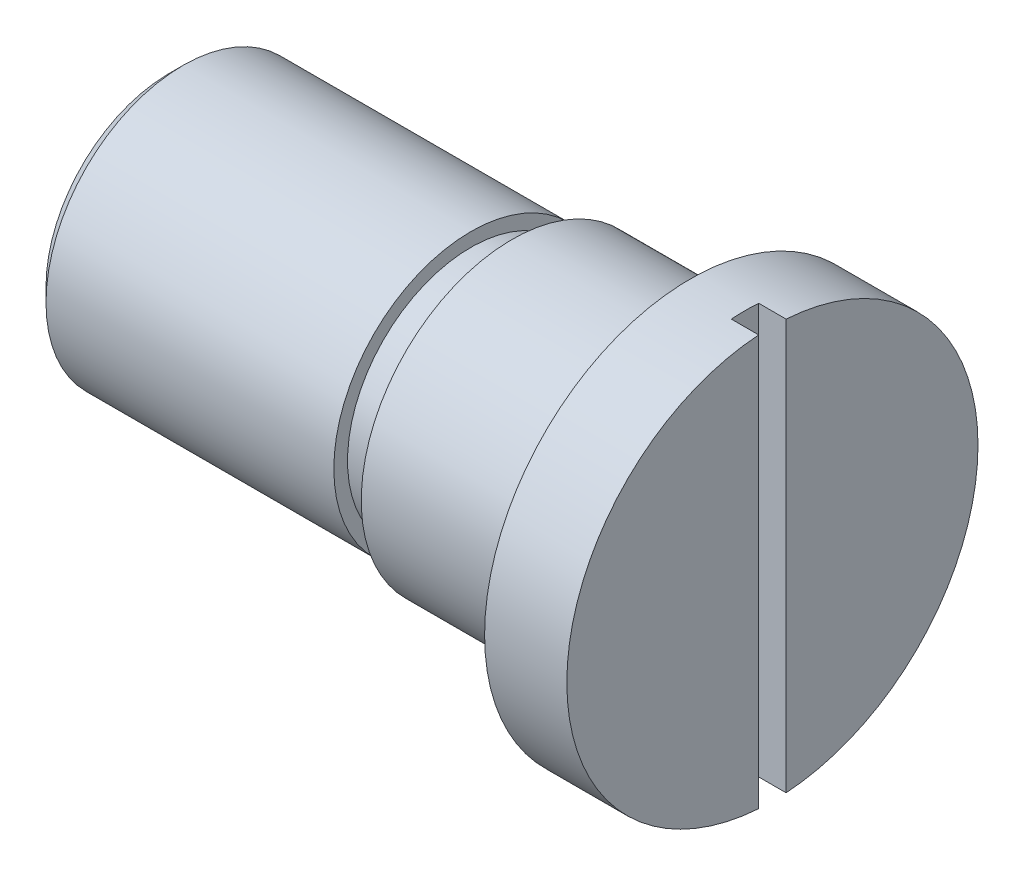
SolidWorks part; units mm, degrees
ref_plane "Ön Düzlem" through (0, 0, 0) normal (0, 0, 1) x (1, 0, 0)
ref_plane "Üst Düzlem" through (0, 0, 0) normal (0, 1, 0) x (1, 0, 0)
ref_plane "Sağ Düzlem" through (0, 0, 0) normal (1, 0, 0) x (0, 0, -1)
sketch "Çizim1" plane through (0, 0, 0) normal (0, 0, 1) x (1, 0, 0)
  line L0 (0, 0) -> (-97.9703, 0) construction
  line L1 (0, 0) -> (0, 15)
  line L2 (0, 15) -> (-6, 15)
  line L3 (-6, 15) -> (-6, 11)
  line L4 (-6, 11) -> (-19, 11)
  line L5 (-19, 11) -> (-19, 9)
  line L6 (-19, 9) -> (-22, 9)
  line L7 (-22, 9) -> (-22, 10)
  line L8 (-22, 10) -> (-44, 10)
  line L9 (-44, 10) -> (-44, 0)
  line L10 (0, 0) -> (-44, 0)
  dimension "D1" = 6
  dimension "D2" = 15
  dimension "D3" = 13
  dimension "D4" = 11
  dimension "D5" = 3
  dimension "D6" = 9
  dimension "D7" = 10
  dimension "D8" = 22
revolve "Döndür1" add sketch "Çizim1" angle 360 about L0
sketch "Çizim2" plane through (0, 0, 0) normal (0, 1, 0) x (1, 0, 0)
  line L0 (0, 0) -> (0, 1)
  line L1 (0, -15) -> (0, 15) construction
  line L2 (0, 1) -> (-2, 1)
  line L3 (-2, 1) -> (-2, -1)
  line L4 (-2, -1) -> (0, -1)
  line L5 (0, -1) -> (0, 0)
  line L6 (0, 0) -> (-5.305, 0) construction
  dimension "D1" = 2
  dimension "D2" = 2
extrude "Kes-Ekstrüzyon1" cut sketch "Çizim2" against normal through all and the other way through all
chamfer "Pah1" distance 1 angle 45 1 edges at (-44, 0, -10)
cosmetic thread "Kozmetik Diş Açma1" parameters "D2"=17.252
